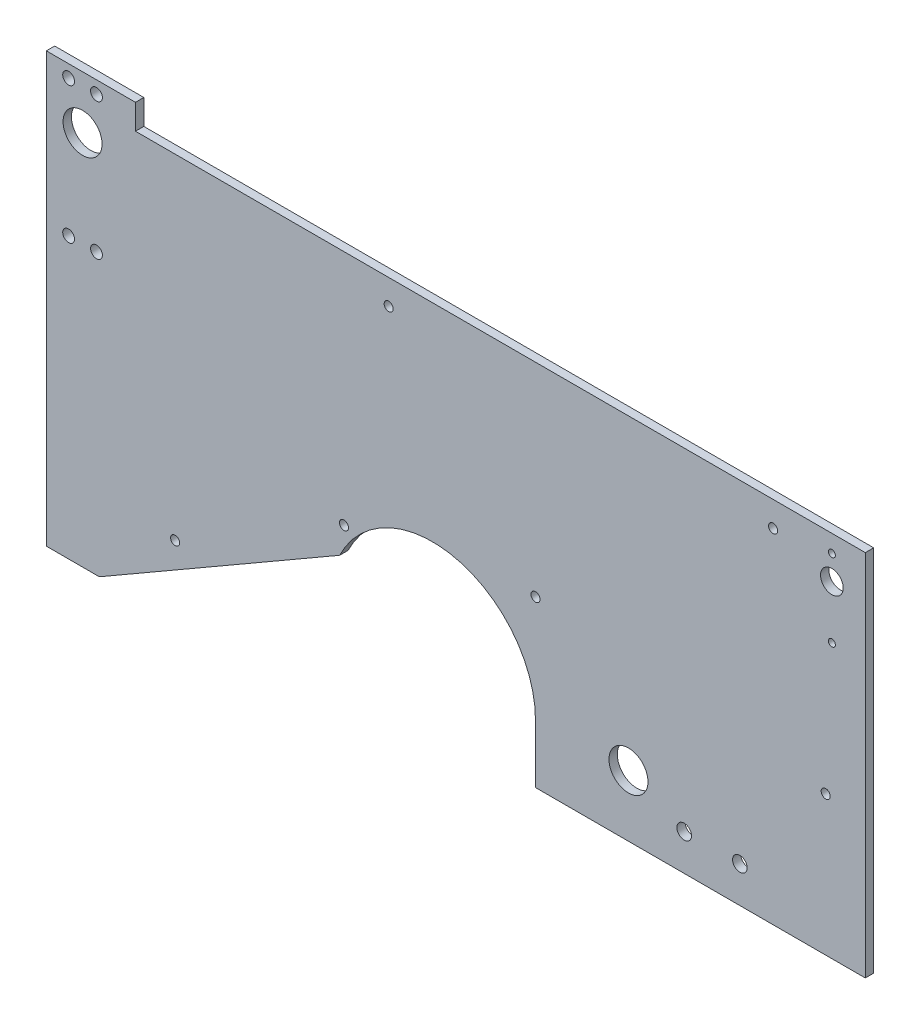
SolidWorks part; units mm, degrees
ref_plane "Front Plane" through (0, 0, 0) normal (0, 0, 1) x (1, 0, 0)
ref_plane "Top Plane" through (0, 0, 0) normal (0, 1, 0) x (1, 0, 0)
ref_plane "Right Plane" through (0, 0, 0) normal (1, 0, 0) x (0, 0, -1)
sketch "Sketch2" plane through (0, 0, 0) normal (0, 0, 1) x (1, 0, 0)
  line L0 (25.0304, 0) -> (111.2865, 49.8)
  line L1 (0, 0) -> (25.0304, 0)
  line L2 (0, 0) -> (0, 154)
  line L4 (300, 0) -> (300, 145)
  line L5 (181.6, 33.7) -> (181.6, 0)
  line L6 (181.6, 0) -> (300, 0)
  line L7 (19, 135) -> (19, 164.3674) construction
  line L11 (38, 145) -> (300, 145)
  line L12 (0, 154) -> (19, 154)
  line L13 (19, 154) -> (38, 154)
  line L14 (38, 154) -> (38, 145)
  line L15 (19, 135) -> (50019, 135) construction
  line L20 (19, 135) -> (19, -49865) construction
  line L21 (24, 149.5) -> (24, -49850.5) construction
  line L22 (14, 149.5) -> (14, -49850.5) construction
  circle A0 centre (19, 135) radius 7
  arc A1 (181.6, 33.7) -> (111.2865, 49.8) centre (144.6, 33.7) ccw
  circle A2 centre (14, 149.5) radius 2.125
  circle A3 centre (24, 149.5) radius 2.125
  circle A4 centre (24, 100.5) radius 2.125
  circle A5 centre (14, 100.5) radius 2.125
  point P19 (19, 154)
  dimension "D3" = 135
  dimension "D4" = 19
  dimension "D5" = 14
  dimension "D6" = 74
  dimension "D7" = 155.4
  dimension "D8" = 33.7
  dimension "D13" = 4.25
  dimension "D14" = 5
  dimension "D15" = 14.5
  dimension "D17" = 49
  dimension "D18" = 4.25
  dimension "D19" = 49
  dimension "D20" = 4.25
  dimension "D1" = 300
  dimension "D2" = 154
  dimension "D9" = 30
  dimension "D10" = 99.6
  dimension "D11" = 19
  dimension "D12" = 145
  dimension "D16" = 9
extrude "Boss-Extrude2" add sketch "Sketch2" along normal blind 3
sketch "Sketch3" plane through (0, 0, 3) normal (0, 0, 1) x (1, 0, 0)
  line L0 (300, 0) -> (300, 145) construction
  line L1 (181.6, 0) -> (300, 0)
  line L2 (181.6, 0) -> (181.6, 12.75)
  line L3 (181.6, 12.75) -> (300, 12.75)
  line L4 (300, 0) -> (300, 12.75)
  dimension "D1" = 12.75
extrude "Cut-Extrude1" cut sketch "Sketch3" against normal through all
sketch "Sketch4" plane through (0, 0, 3) normal (0, 0, 1) x (1, 0, 0)
  line L0 (19, 135) -> (19, -49865) construction
  line L1 (19, 135) -> (-49981, 135) construction
sketch "Sketch5" plane through (0, 0, 3) normal (0, 0, 1) x (1, 0, 0)
  line L0 (300, 12.75) -> (300, 145) construction
  line L1 (300, 12.75) -> (181.6, 12.75) construction
  line L2 (300, 145) -> (38, 145) construction
  line L3 (0, 154) -> (0, 0) construction
  line L4 (0, 0) -> (25.0304, 0) construction
  line L6 (0, 154) -> (6, 154)
  line L7 (0, 154) -> (0, 0)
  line L8 (0, 0) -> (6, 0)
  line L9 (6, 154) -> (6, 0)
  circle A0 centre (254.98, 25.75) radius 2.625
  circle A1 centre (234.98, 25.75) radius 2.625
  circle A2 centre (288, 130) radius 4.075
  circle A3 centre (288, 138.75) radius 1.25
  circle A4 centre (288, 110.95) radius 1.25
  circle A7 centre (285.78, 62.92) radius 1.625
  circle A8 centre (181.6, 72.03) radius 1.625
  circle A9 centre (52.23, 24.91) radius 1.625
  circle A10 centre (112.84, 59.93) radius 1.625
  circle A11 centre (266.895, 135.995) radius 1.625
  circle A12 centre (128.895, 135.995) radius 1.625
  circle A13 centre (214.98, 34.75) radius 7
  dimension "D1" = 45.02
  dimension "D2" = 13
  dimension "D3" = 20
  dimension "D4" = 13
  dimension "D5" = 5.25
  dimension "D6" = 5.25
  dimension "D7" = 8.15
  dimension "D8" = 15
  dimension "D9" = 2.5
  dimension "D10" = 8.75
  dimension "D11" = 27.8
  dimension "D12" = 2.5
  dimension "D13" = 12
  dimension "D14" = 12
  dimension "D15" = 12
  dimension "D16" = 82.08
  dimension "D17" = 3.25
  dimension "D18" = 14.22
  dimension "D19" = 72.97
  dimension "D20" = 3.25
  dimension "D21" = 118.4
  dimension "D22" = 3.25
  dimension "D23" = 52.23
  dimension "D24" = 24.91
  dimension "D25" = 3.25
  dimension "D26" = 112.84
  dimension "D27" = 59.93
  dimension "D28" = 3.25
  dimension "D29" = 9.005
  dimension "D30" = 33.105
  dimension "D31" = 3.25
  dimension "D32" = 138
  dimension "D33" = 9.005
  dimension "D34" = 27.8
  dimension "D36" = 14
  dimension "D37" = 22
  dimension "D38" = 20
  dimension "D35" = 6
extrude "Cut-Extrude2" cut sketch "Sketch5" against normal through all
